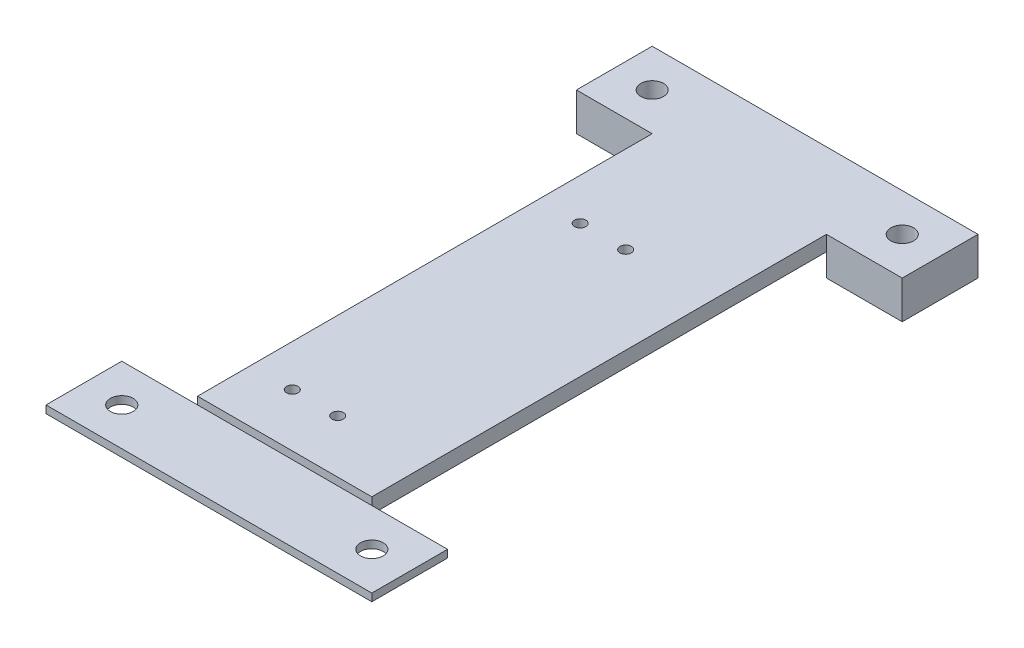
SolidWorks part; units mm, degrees
ref_plane "Front Plane" through (0, 0, 0) normal (0, 0, 1) x (1, 0, 0)
ref_plane "Top Plane" through (0, 0, 0) normal (0, 1, 0) x (1, 0, 0)
ref_plane "Right Plane" through (0, 0, 0) normal (1, 0, 0) x (0, 0, -1)
sketch "Sketch1" plane through (0, 0, 0) normal (0, 1, 0) x (1, 0, 0)
  line L1 (0, 140) -> (86, 140)
  line L8 (0, 140) -> (0, 120)
  line L9 (0, 120) -> (20, 120)
  line L10 (20, 120) -> (20, 0)
  line L11 (86, 140) -> (86, 120)
  line L12 (86, 120) -> (66, 120)
  line L13 (66, 120) -> (66, 0)
  line L14 (66, 0) -> (20, 0)
  circle A0 centre (10, 130) radius 3
  circle A1 centre (76, 130) radius 3
  dimension "D6" = 6
  dimension "D7" = 6
  dimension "D8" = 10
  dimension "D9" = 20
  dimension "D10" = 10
  dimension "D11" = 20
  dimension "D1" = 86
  dimension "D2" = 20
  dimension "D5" = 120
extrude "Boss-Extrude1" add sketch "Sketch1" along normal blind 4
sketch "Sketch8" plane through (0, 0, 0) normal (0, -1, 0) x (1, 0, 0)
  line L1 (0, -140) -> (20, -140)
  line L2 (0, -140) -> (0, -120)
  line L3 (0, -120) -> (20, -120)
  line L4 (20, -140) -> (20, -120)
  line L5 (86, -140) -> (66, -140)
  line L6 (86, -140) -> (86, -120)
  line L7 (86, -120) -> (66, -120)
  line L8 (66, -140) -> (66, -120)
  circle A2 centre (10, -130) radius 3
  circle A3 centre (76, -130) radius 3
extrude "Boss-Extrude3" add sketch "Sketch8" along normal blind 6
sketch "Sketch9" plane through (0, 4, 0) normal (0, 1, 0) x (1, 0, 0)
  line L0 (0, 140) -> (0, 120) construction
  line L2 (0, 120) -> (20, 120) construction
  circle A0 centre (31, 90) radius 1.5
  circle A1 centre (43, 90) radius 1.5
  circle A2 centre (31, 14) radius 1.5
  circle A3 centre (43, 14) radius 1.5
  dimension "D1" = 3
  dimension "D2" = 3
  dimension "D3" = 3
  dimension "D4" = 3
  dimension "D9" = 30
  dimension "D10" = 76
  dimension "D12" = 76
  dimension "D5" = 31
  dimension "D6" = 43
  dimension "D7" = 31
  dimension "D8" = 43
  dimension "D11" = 30
extrude "Cut-Extrude5" cut sketch "Sketch9" against normal blind 6
sketch "Sketch10" plane through (0, 0, 0) normal (0, 0, 1) x (1, 0, 0)
  line L0 (66, 4) -> (66, 0) construction
  line L1 (20, 0) -> (66, 0)
  line L2 (20, 0) -> (20, 2)
  line L3 (20, 2) -> (66, 2)
  line L4 (66, 0) -> (66, 2)
extrude "Boss-Extrude4" add sketch "Sketch10" along normal blind 20
sketch "Sketch13" plane through (66, 0, 0) normal (1, 0, 0) x (0, 0, -1)
  line L1 (-20, 2) -> (0, 2)
  line L2 (-20, 2) -> (-20, 0)
  line L3 (-20, 0) -> (0, 0)
  line L4 (0, 2) -> (0, 0)
extrude "Boss-Extrude5" add sketch "Sketch13" along normal blind 20
sketch "Sketch14" plane through (20, 0, 0) normal (-1, 0, 0) x (0, 0, 1)
  line L1 (20, 0) -> (0, 0)
  line L2 (20, 0) -> (20, 2)
  line L3 (20, 2) -> (0, 2)
  line L4 (0, 0) -> (0, 2)
extrude "Boss-Extrude7" add sketch "Sketch14" along normal blind 20
sketch "Sketch15" plane through (0, 2, 0) normal (0, 1, 0) x (1, 0, 0)
  line L0 (86, -20) -> (0, -20) construction
  line L1 (0, -20) -> (0, 0) construction
  line L2 (86, 0) -> (86, -20) construction
  circle A0 centre (10, -10) radius 3
  circle A1 centre (76, -10) radius 3
  dimension "D1" = 6
  dimension "D2" = 6
  dimension "D3" = 10
  dimension "D4" = 10
  dimension "D5" = 10
  dimension "D6" = 10
extrude "Cut-Extrude7" cut sketch "Sketch15" against normal blind 20
